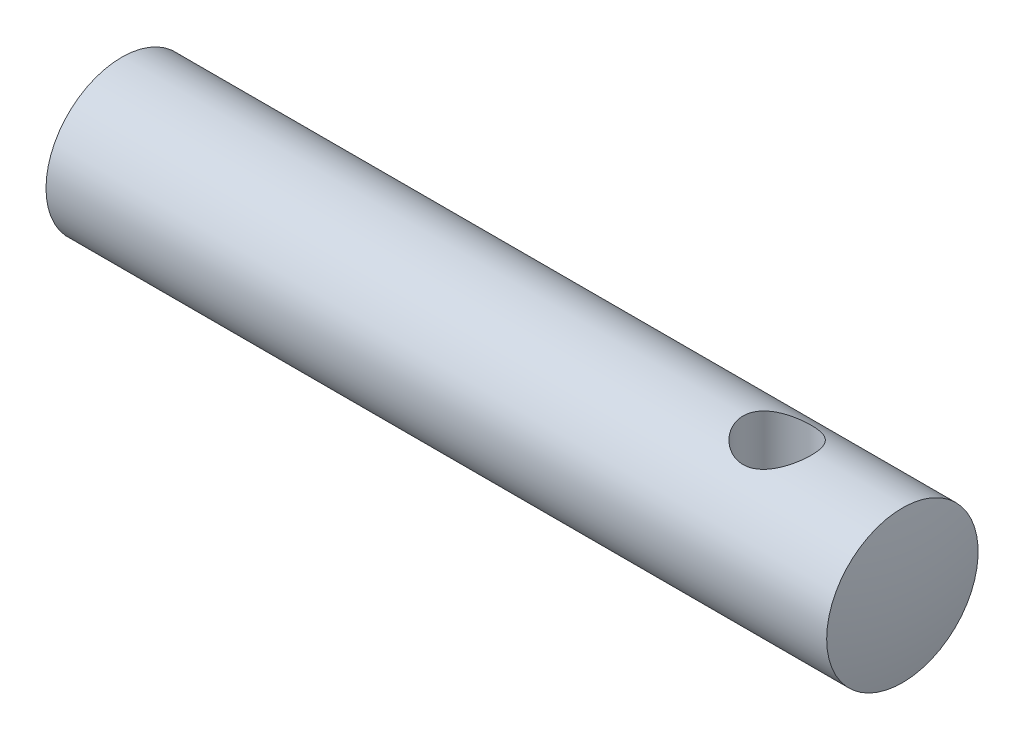
SolidWorks part; units mm, degrees
ref_plane "Piano frontale" through (0, 0, 0) normal (0, 0, 1) x (1, 0, 0)
ref_plane "Piano superiore" through (0, 0, 0) normal (0, 1, 0) x (1, 0, 0)
ref_plane "Piano destro" through (0, 0, 0) normal (1, 0, 0) x (0, 0, -1)
sketch "Schizzo2" plane through (0, 0, 0) normal (0, 1, 0) x (1, 0, 0)
  line L1 (-10.5, 2) -> (10.5, 2)
  line L2 (-10.5, 2) -> (-10.5, -2)
  line L3 (-10.5, -2) -> (10.5, -2)
  line L4 (10.5, 2) -> (10.5, -2)
  line L5 (-10.5, 0) -> (10.5, 0)
  circle A0 centre (0, 0) radius 10.5
  dimension "D1" = 21
  dimension "D2" = 4
  dimension "D3" = 2
revolve "Rivoluzione1" add sketch "Schizzo2" angle 360 about L5
sketch "Schizzo3" plane through (0, 0, 0) normal (0, 1, 0) x (1, 0, 0)
  circle A0 centre (7, 0) radius 0.9
  point P2 (0, 0)
  dimension "D2" = 1.8
  dimension "D1" = 7
extrude "Taglio-Estrusione2" cut sketch "Schizzo3" against normal through all both and the other way through all
